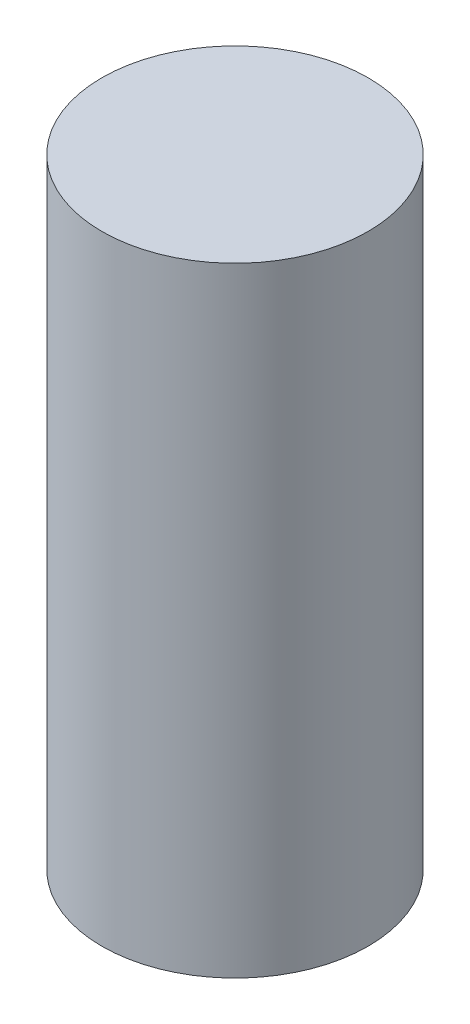
SolidWorks part; units mm, degrees
ref_plane "Front Plane" through (0, 0, 0) normal (0, 0, 1) x (1, 0, 0)
ref_plane "Top Plane" through (0, 0, 0) normal (0, 1, 0) x (1, 0, 0)
ref_plane "Right Plane" through (0, 0, 0) normal (1, 0, 0) x (0, 0, -1)
sketch "Sketch1" plane through (0, 0, 0) normal (0, 1, 0) x (1, 0, 0)
  circle A0 centre (-13.4854, 9.7835) radius 32.2591
extrude "Boss-Extrude1" add sketch "Sketch1" along normal blind 150
